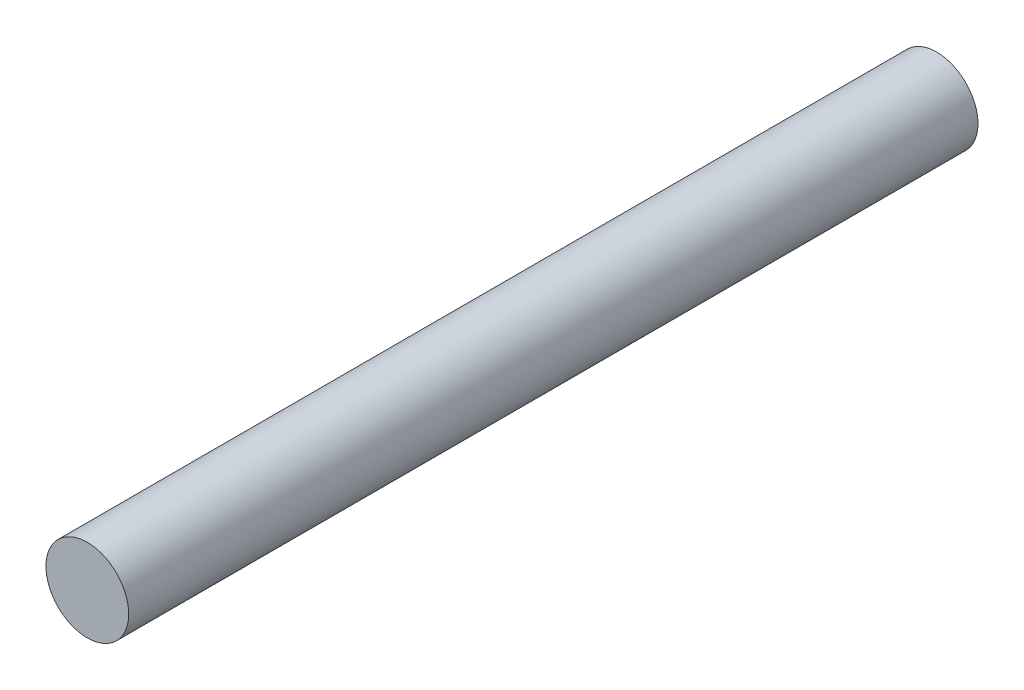
SolidWorks part; units mm, degrees
ref_plane "Front Plane" through (0, 0, 0) normal (0, 0, 1) x (1, 0, 0)
ref_plane "Top Plane" through (0, 0, 0) normal (0, 1, 0) x (1, 0, 0)
ref_plane "Right Plane" through (0, 0, 0) normal (1, 0, 0) x (0, 0, -1)
sketch "Sketch1" plane through (0, 0, 0) normal (0, 0, 1) x (1, 0, 0)
  circle A0 centre (0, 0) radius 0.7366
  dimension "D1" = 1.4732
extrude "Boss-Extrude1" add sketch "Sketch1" along normal blind 15.113
